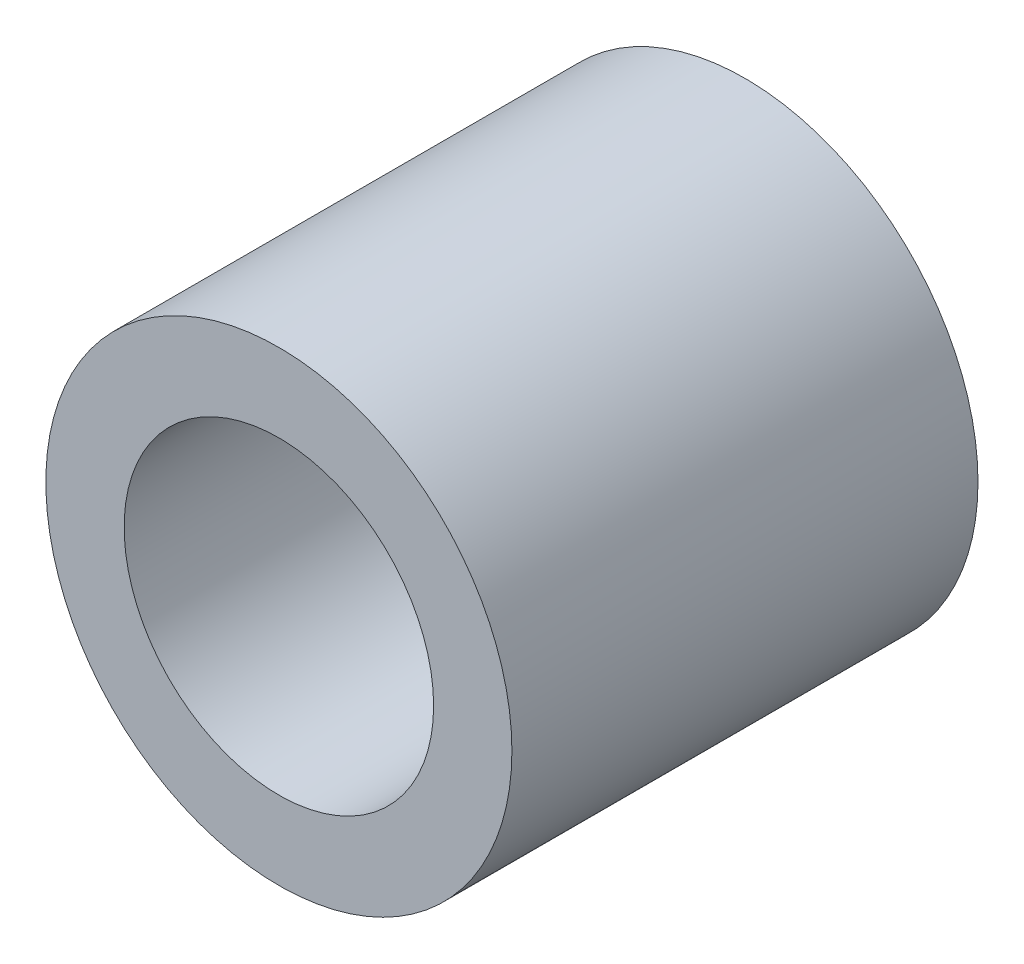
SolidWorks part; units mm, degrees
ref_plane "Front Plane" through (0, 0, 0) normal (0, 0, 1) x (1, 0, 0)
ref_plane "Top Plane" through (0, 0, 0) normal (0, 1, 0) x (1, 0, 0)
ref_plane "Right Plane" through (0, 0, 0) normal (1, 0, 0) x (0, 0, -1)
sketch "Sketch1" plane through (0, 0, 0) normal (0, 0, 1) x (1, 0, 0)
  circle A0 centre (0, 0) radius 3.175
  circle A1 centre (0, 0) radius 2.1082
  dimension "OD" = 6.35
  dimension "ID" = 4.2164
extrude "Extrude1" add sketch "Sketch1" along normal mid plane 6.35
sketch "Sketch2" plane through (0, 0, 0) normal (1, 0, 0) x (0, 0, -1)
  line L0 (-3.175, -2.1082) -> (3.175, -2.1082) construction
  line L3 (3.175, 2.1082) -> (-3.175, 2.1082) construction
  line L5 (-3.175, -2.1082) -> (3.175, -2.1082)
  line L6 (3.175, 2.1082) -> (-3.175, 2.1082)
sketch "Sketch4" plane through (0, 0, 3.175) normal (0, 0, 1) x (1, 0, 0)
  line L0 (0, 0) -> (-1.4907, 1.4907)
  line L1 (0, -2.1828) -> (0, 2.1828) construction
  circle A0 centre (0, 0) radius 2.1082 construction
  dimension "D1" = 45
